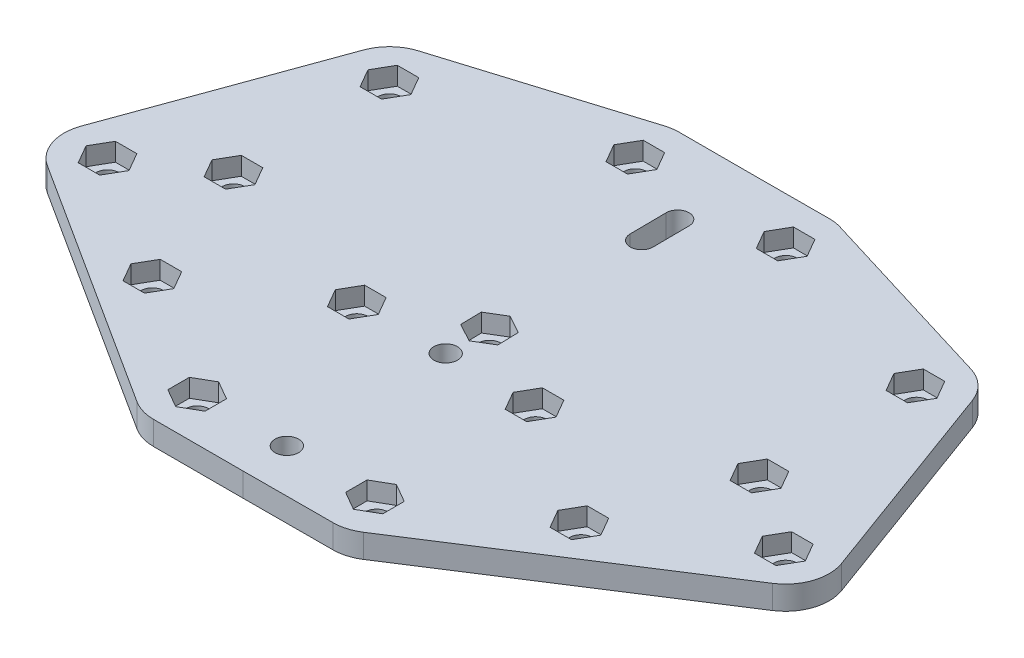
SolidWorks part; units mm, degrees
ref_plane "Front Plane" through (0, 0, 0) normal (0, 0, 1) x (1, 0, 0)
ref_plane "Top Plane" through (0, 0, 0) normal (0, 1, 0) x (1, 0, 0)
ref_plane "Right Plane" through (0, 0, 0) normal (1, 0, 0) x (0, 0, -1)
sketch "DimensionalReference" plane through (0, 0, 0) normal (0, 1, 0) x (1, 0, 0)
  line L0 (0, 0) -> (0, 54.3246) construction
  line L1 (-1000, 12.5) -> (1000, 12.5) construction
  line L2 (-1000, 12.5) -> (-1000, -12.5) construction
  line L3 (-1000, -12.5) -> (1000, -12.5) construction
  line L4 (1000, 12.5) -> (1000, -12.5) construction
  line L5 (-72.5, -22.5) -> (-72.5, 60.05) construction
  line L6 (0, 22.5) -> (0, -109.2175) construction
  line L7 (-12.5, -17.5) -> (12.9, -17.5) construction
  line L8 (-12.5, -17.5) -> (-12.5, -92.5) construction
  line L9 (-12.5, -92.5) -> (12.9, -92.5) construction
  line L10 (12.9, -17.5) -> (12.9, -92.5) construction
  line L11 (-104.4908, -32.4017) -> (-83.7785, 24.5983)
  line L12 (-23.5771, 48.153) -> (-76.0379, 31.9666)
  line L13 (-20.7123, 48.5) -> (20.7123, 48.5)
  line L14 (-93.2123, -36.5) -> (-24.5, -80.5) construction
  line L15 (-24.5, -80.5) -> (24.5, -80.5) construction
  line L16 (93.2123, -36.5) -> (24.5, -80.5) construction
  line L17 (104.4908, -32.4017) -> (83.7785, 24.5983)
  line L18 (23.5771, 48.153) -> (76.0379, 31.9666)
  line L19 (-12.5, -92.5) -> (-24.5, -92.5)
  line L20 (-99.6835, -46.6056) -> (-65.3273, -68.6056)
  line L21 (-65.3273, -68.6056) -> (-30.9712, -90.6056)
  line L22 (0.2, -92.5) -> (-12.5, -92.5)
  line L23 (99.6835, -46.6056) -> (65.3273, -68.6056)
  line L24 (65.3273, -68.6056) -> (30.9712, -90.6056)
  line L25 (12.5, -92.5) -> (24.5, -92.5)
  line L26 (-0.2, -92.5) -> (12.5, -92.5)
  circle A0 centre (0, 22.5) radius 12 construction
  circle A1 centre (-72.5, -22.5) radius 12 construction
  circle A2 centre (72.5, -22.5) radius 12 construction
  circle A3 centre (0, 22.5) radius 15 construction
  circle A4 centre (-72.5, -22.5) radius 15 construction
  circle A5 centre (72.5, -22.5) radius 15 construction
  circle A6 centre (0, 22.5) radius 25
  circle A7 centre (-72.5, -22.5) radius 25
  circle A8 centre (72.5, -22.5) radius 25
  circle A9 centre (-72.5, 20.5) radius 12
  circle A10 centre (-72.5, 20.5) radius 3.25
  circle A11 centre (-93.2123, -36.5) radius 12
  circle A12 centre (-20.7123, 36.5) radius 12
  circle A13 centre (-24.5, -36.5) radius 12
  circle A16 centre (72.5, 20.5) radius 12
  circle A17 centre (93.2123, -36.5) radius 12
  circle A18 centre (24.5, -36.5) radius 12
  circle A19 centre (20.7123, 36.5) radius 12
  circle A20 centre (-24.5, -80.5) radius 12
  circle A21 centre (24.5, -80.5) radius 12
  circle A22 centre (-58.8562, -58.5) radius 12
  circle A23 centre (58.8562, -58.5) radius 12
  point P0 (0, 0)
  point P24 (0, -262.4926)
  point P39 (0, 48.5)
  point P47 (0, -48.5)
  dimension "D3" = 24
  dimension "D10" = 24
  dimension "D11" = 24
  dimension "D13" = 30
  dimension "D14" = 30
  dimension "D15" = 30
  dimension "D16" = 50
  dimension "D17" = 50
  dimension "D18" = 50
  dimension "D19" = 24
  dimension "D21" = 6.5
  dimension "D22" = 24
  dimension "D29" = 24
  dimension "D31" = 12
  dimension "D32" = 12
  dimension "D1" = 2000
  dimension "D2" = 25
  dimension "D4" = 22.5
  dimension "D5" = 12.5
  dimension "D6" = 1000
  dimension "D7" = 145
  dimension "D8" = 72.5
  dimension "D9" = 22.5
  dimension "D12" = 22.5
  dimension "D20" = 8
  dimension "D23" = 24
  dimension "D24" = 24
  dimension "D25" = 25.4
  dimension "D26" = 75
  dimension "D27" = 12.5
  dimension "D28" = 5
  dimension "D30" = 12
sketch "Sketch2" plane through (0, 0, 0) normal (0, 1, 0) x (1, 0, 0)
  line L0 (24.8999, -92.4299) -> (0.2, -92.5)
  line L1 (-104.4908, -32.4017) -> (-83.7785, 24.5983)
  line L2 (-76.0379, 31.9666) -> (-24.9114, 47.7413)
  line L3 (0, 48.5) -> (-20.7123, 48.5)
  line L4 (-99.6835, -46.6056) -> (-30.9712, -90.6056)
  line L5 (0, 48.5) -> (0.2, -92.5) construction
  line L6 (-24.5, -92.5) -> (0.2, -92.5)
  line L7 (99.9529, -46.3225) -> (31.3657, -90.5172)
  line L8 (0, 48.5) -> (20.7122, 48.5588)
  line L9 (76.0845, 32.1824) -> (24.9134, 47.812)
  line L10 (104.7199, -32.1049) -> (83.8459, 24.8361)
  line L11 (-0.044, 27.5) -> (0.044, 17.5) construction
  line L12 (3.1059, 27.5277) -> (3.1938, 17.5277)
  line L13 (-3.1938, 27.4723) -> (-3.1059, 17.4723)
  line L28 (-24.5, -36.5) -> (24.5, -36.5) construction
  line L29 (-24.5, -80.5) -> (24.8659, -80.43) construction
  line L30 (0, 0) -> (139.3739, 0) construction
  arc A0 (-20.7123, 48.5) -> (-24.9114, 47.7413) centre (-20.7123, 36.5) ccw
  arc A6 (-30.9712, -90.6056) -> (-24.5, -92.5) centre (-24.5, -80.5) ccw
  arc A8 (-104.4908, -32.4017) -> (-99.6835, -46.6056) centre (-93.2123, -36.5) ccw
  arc A10 (-76.0379, 31.9666) -> (-83.7785, 24.5983) centre (-72.5, 20.5) ccw
  arc A11 (104.7199, -32.1049) -> (99.9529, -46.3225) centre (93.4531, -36.2352) cw
  arc A12 (76.0845, 32.1824) -> (83.8459, 24.8361) centre (72.5791, 20.7058) cw
  arc A13 (31.3657, -90.5172) -> (24.8999, -92.4299) centre (24.8659, -80.43) cw
  arc A14 (20.7122, 48.5588) -> (24.9134, 47.812) centre (20.7463, 36.5588) cw
  circle A15 centre (-72.5, 20.5) radius 3.15
  circle A16 centre (-20.7123, 36.5) radius 3.15
  circle A17 centre (-93.2123, -36.5) radius 3.15
  circle A18 centre (-58.8562, -58.5) radius 3.15
  circle A19 centre (-24.5, -80.5) radius 3.15
  circle A20 centre (-24.5, -36.5) radius 3.15
  circle A21 centre (-72.5, -22.5) radius 3.15
  arc A23 (3.1059, 27.5277) -> (-3.1938, 27.4723) centre (-0.044, 27.5) ccw
  arc A24 (-3.1059, 17.4723) -> (3.1938, 17.5277) centre (0.044, 17.5) ccw
  circle A25 centre (24.741, -36.4302) radius 3.15
  circle A26 centre (24.8659, -80.43) radius 3.15
  circle A27 centre (59.1595, -58.3326) radius 3.15
  circle A28 centre (93.4531, -36.2352) radius 3.15
  circle A29 centre (72.7011, -22.294) radius 3.15
  circle A30 centre (72.5791, 20.7058) radius 3.15
  circle A31 centre (20.7463, 36.5588) radius 3.15
  circle A32 centre (0, -36.5) radius 3.25
  circle A33 centre (0.1829, -80.465) radius 3.25
  circle A36 centre (0.1035, -24.5) radius 3.1
  point P22 (0, 22.5)
  dimension "D1" = 6.3
  dimension "D2" = 3.15
  dimension "D6" = 6.5
  dimension "D7" = 6.5
  dimension "D4" = 6.2
  dimension "D3" = 10
  dimension "D5" = 12
extrude "MainPlate" add sketch "Sketch2" along normal blind 6.5
sketch "Sketch8" plane through (0, 6.5, 0) normal (0, 1, 0) x (1, 0, 0)
  line L7 (-4.8355, -27.4899) -> (0.2234, -30.2723)
  line L8 (0.2234, -30.2723) -> (5.1624, -27.2824)
  line L9 (-18.5822, -36.5) -> (-21.5411, -31.375)
  line L10 (-21.5411, -31.375) -> (-27.4589, -31.375)
  line L11 (-27.4589, -31.375) -> (-30.4178, -36.5)
  line L12 (-30.4178, -36.5) -> (-27.4589, -41.625)
  line L13 (-27.4589, -41.625) -> (-21.5411, -41.625)
  line L14 (-21.5411, -41.625) -> (-18.5822, -36.5)
  line L15 (-66.5822, -22.5) -> (-69.5411, -17.375)
  line L16 (-69.5411, -17.375) -> (-75.4589, -17.375)
  line L17 (-75.4589, -17.375) -> (-78.4178, -22.5)
  line L18 (-78.4178, -22.5) -> (-75.4589, -27.625)
  line L19 (-75.4589, -27.625) -> (-69.5411, -27.625)
  line L20 (-69.5411, -27.625) -> (-66.5822, -22.5)
  line L21 (-66.5822, 20.5) -> (-69.5411, 25.625)
  line L22 (-69.5411, 25.625) -> (-75.4589, 25.625)
  line L23 (-75.4589, 25.625) -> (-78.4178, 20.5)
  line L24 (-78.4178, 20.5) -> (-75.4589, 15.375)
  line L25 (-75.4589, 15.375) -> (-69.5411, 15.375)
  line L26 (-69.5411, 15.375) -> (-66.5822, 20.5)
  line L27 (-87.2945, -36.5) -> (-90.2534, -31.375)
  line L28 (-90.2534, -31.375) -> (-96.1712, -31.375)
  line L29 (-96.1712, -31.375) -> (-99.1302, -36.5)
  line L30 (-99.1302, -36.5) -> (-96.1712, -41.625)
  line L31 (-96.1712, -41.625) -> (-90.2534, -41.625)
  line L32 (-90.2534, -41.625) -> (-87.2945, -36.5)
  line L33 (-52.9383, -58.5) -> (-55.8972, -53.375)
  line L34 (-55.8972, -53.375) -> (-61.8151, -53.375)
  line L35 (-61.8151, -53.375) -> (-64.774, -58.5)
  line L36 (-64.774, -58.5) -> (-61.8151, -63.625)
  line L37 (-61.8151, -63.625) -> (-55.8972, -63.625)
  line L38 (-55.8972, -63.625) -> (-52.9383, -58.5)
  line L39 (-24.5, -74.5822) -> (-29.625, -77.5411)
  line L40 (-29.625, -77.5411) -> (-29.625, -83.4589)
  line L41 (-29.625, -83.4589) -> (-24.5, -86.4178)
  line L42 (-24.5, -86.4178) -> (-19.375, -83.4589)
  line L43 (-19.375, -83.4589) -> (-19.375, -77.5411)
  line L44 (-19.375, -77.5411) -> (-24.5, -74.5822)
  line L45 (-14.7945, 36.5) -> (-17.7534, 41.625)
  line L46 (-17.7534, 41.625) -> (-23.6712, 41.625)
  line L47 (-23.6712, 41.625) -> (-26.6302, 36.5)
  line L48 (-26.6302, 36.5) -> (-23.6712, 31.375)
  line L49 (-23.6712, 31.375) -> (-17.7534, 31.375)
  line L50 (-17.7534, 31.375) -> (-14.7945, 36.5)
  line L51 (17.7534, 31.375) -> (14.7945, 36.5)
  line L52 (23.6712, 31.375) -> (17.7534, 31.375)
  line L53 (26.6302, 36.5) -> (23.6712, 31.375)
  line L54 (23.6712, 41.625) -> (26.6302, 36.5)
  line L55 (17.7534, 41.625) -> (23.6712, 41.625)
  line L56 (14.7945, 36.5) -> (17.7534, 41.625)
  line L57 (19.375, -77.5411) -> (24.5, -74.5822)
  line L58 (19.375, -83.4589) -> (19.375, -77.5411)
  line L59 (24.5, -86.4178) -> (19.375, -83.4589)
  line L60 (29.625, -83.4589) -> (24.5, -86.4178)
  line L61 (29.625, -77.5411) -> (29.625, -83.4589)
  line L62 (24.5, -74.5822) -> (29.625, -77.5411)
  line L63 (55.8972, -63.625) -> (52.9383, -58.5)
  line L64 (61.8151, -63.625) -> (55.8972, -63.625)
  line L65 (64.774, -58.5) -> (61.8151, -63.625)
  line L66 (61.8151, -53.375) -> (64.774, -58.5)
  line L67 (55.8972, -53.375) -> (61.8151, -53.375)
  line L68 (52.9383, -58.5) -> (55.8972, -53.375)
  line L69 (90.2534, -41.625) -> (87.2945, -36.5)
  line L70 (96.1712, -41.625) -> (90.2534, -41.625)
  line L71 (99.1302, -36.5) -> (96.1712, -41.625)
  line L72 (96.1712, -31.375) -> (99.1302, -36.5)
  line L73 (90.2534, -31.375) -> (96.1712, -31.375)
  line L74 (87.2945, -36.5) -> (90.2534, -31.375)
  line L75 (69.5411, 15.375) -> (66.5822, 20.5)
  line L76 (75.4589, 15.375) -> (69.5411, 15.375)
  line L77 (78.4178, 20.5) -> (75.4589, 15.375)
  line L78 (75.4589, 25.625) -> (78.4178, 20.5)
  line L79 (69.5411, 25.625) -> (75.4589, 25.625)
  line L80 (66.5822, 20.5) -> (69.5411, 25.625)
  line L81 (69.5411, -27.625) -> (66.5822, -22.5)
  line L82 (75.4589, -27.625) -> (69.5411, -27.625)
  line L83 (78.4178, -22.5) -> (75.4589, -27.625)
  line L84 (75.4589, -17.375) -> (78.4178, -22.5)
  line L85 (69.5411, -17.375) -> (75.4589, -17.375)
  line L86 (66.5822, -22.5) -> (69.5411, -17.375)
  line L87 (21.5411, -41.625) -> (18.5822, -36.5)
  line L88 (27.4589, -41.625) -> (21.5411, -41.625)
  line L89 (30.4178, -36.5) -> (27.4589, -41.625)
  line L90 (27.4589, -31.375) -> (30.4178, -36.5)
  line L91 (21.5411, -31.375) -> (27.4589, -31.375)
  line L92 (18.5822, -36.5) -> (21.5411, -31.375)
  line L93 (5.1624, -27.2824) -> (5.0426, -21.5101)
  line L94 (5.0426, -21.5101) -> (-0.0163, -18.7277)
  line L95 (-0.0163, -18.7277) -> (-4.9553, -21.7176)
  line L96 (-4.9553, -21.7176) -> (-4.8355, -27.4899)
  circle A0 centre (0.1035, -24.5) radius 5 construction
  circle A1 centre (-24.5, -36.5) radius 5.125 construction
  circle A2 centre (-72.5, -22.5) radius 5.125 construction
  circle A3 centre (-72.5, 20.5) radius 5.125 construction
  circle A4 centre (-93.2123, -36.5) radius 5.125 construction
  circle A5 centre (-58.8562, -58.5) radius 5.125 construction
  circle A6 centre (-24.5, -80.5) radius 5.125 construction
  circle A7 centre (-20.7123, 36.5) radius 5.125 construction
  circle A8 centre (20.7123, 36.5) radius 5.125 construction
  circle A9 centre (24.5, -80.5) radius 5.125 construction
  circle A10 centre (58.8562, -58.5) radius 5.125 construction
  circle A11 centre (93.2123, -36.5) radius 5.125 construction
  circle A12 centre (72.5, 20.5) radius 5.125 construction
  circle A13 centre (72.5, -22.5) radius 5.125 construction
  circle A14 centre (24.5, -36.5) radius 5.125 construction
  point P2 (2.6929, -28.7773)
  dimension "D1" = 10
  dimension "D2" = 10.25
  dimension "D3" = 10.25
  dimension "D4" = 10.25
  dimension "D5" = 10.25
  dimension "D6" = 10.25
  dimension "D7" = 10.25
  dimension "D8" = 10.25
extrude "PressFitNuts" cut sketch "Sketch8" against normal blind 5
sketch "Sketch9" plane through (0, 6.5, 0) normal (0, 1, 0) x (1, 0, 0)
  line L0 (52.6627, -41.5446) -> (50.906, -42.448)
  line L1 (46.1928, -40.9361) -> (17.801, 14.2744)
  line L2 (20.9136, 19.375) -> (51.1306, 19.375)
  line L3 (54.6306, 15.8706) -> (54.562, -38.4365)
  line L4 (0.2, -92.5) -> (0.1035, -24.5) construction
  line L5 (0, 48.5) -> (-20.7123, 48.5) construction
  line L8 (1.0348, -68.2409) -> (25.7237, -61.874)
  line L9 (25.7235, -55.0957) -> (1.0165, -48.7258)
  line L10 (75.4589, -17.375) -> (69.5411, -17.375) construction
  line L11 (17.7534, 31.375) -> (23.6712, 31.375) construction
  line L12 (104.7199, -32.1049) -> (83.8459, 24.8361) construction
  line L13 (3.1938, 17.5277) -> (3.1059, 27.5277) construction
  line L14 (72.4743, -5.375) -> (70.1082, -5.375)
  line L15 (66.6082, -1.8706) -> (66.6107, 0.0995)
  line L16 (72.3516, 2.7836) -> (74.7152, 0.8136)
  line L21 (73.0837, -41.5737) -> (69.4223, -40.2688)
  line L22 (68.257, -41.7691) -> (72.4275, -47.9662)
  line L23 (74.1008, -47.9448) -> (74.8613, -46.7499)
  line L24 (87.2945, -36.5) -> (90.2534, -41.625) construction
  line L25 (64.774, -58.5) -> (61.8151, -53.375) construction
  line L26 (31.3657, -90.5172) -> (99.9529, -46.3225) construction
  line L27 (-73.8269, -48.1547) -> (-74.5908, -46.9619)
  line L28 (-68.0006, -41.9624) -> (-72.1536, -48.1713)
  line L29 (-72.8278, -41.7807) -> (-69.1702, -40.4654)
  line L31 (-72.2216, 2.5786) -> (-74.5796, 0.6018)
  line L32 (-66.465, -2.0593) -> (-66.4731, -0.0893)
  line L33 (-72.3212, -5.5804) -> (-69.9551, -5.5737)
  line L34 (-25.4295, -55.1682) -> (-0.7407, -48.7283)
  line L35 (-0.7036, -68.2434) -> (-25.4105, -61.9465)
  line L38 (-54.5378, 15.7157) -> (-54.3152, -38.5909)
  line L39 (-20.8309, 19.3158) -> (-51.0478, 19.2301)
  line L40 (-45.9389, -41.0668) -> (-17.7039, 14.224)
  line L41 (-52.407, -41.6937) -> (-50.6478, -42.5921)
  line L42 (0.0562, 8.8531) -> (0, 48.5) construction
  circle A0 centre (0, -36.5) radius 3.25 construction
  circle A1 centre (0.1829, -80.465) radius 3.25 construction
  circle A2 centre (0.1829, -80.465) radius 3.25 construction
  circle A3 centre (0.2411, -36.4997) radius 3.25 construction
  arc A4 (-20.8309, 19.3158) -> (-17.7039, 14.224) centre (-20.821, 15.8158) cw
  arc A5 (-54.5378, 15.7157) -> (-51.0478, 19.2301) centre (-51.0378, 15.7301) cw
  arc A6 (-74.5796, 0.6018) -> (-72.3212, -5.5804) centre (-72.3311, -2.0804) ccw
  arc A7 (-72.2216, 2.5786) -> (-66.4731, -0.0893) centre (-69.9731, -0.1036) cw
  arc A8 (-66.465, -2.0593) -> (-69.9551, -5.5737) centre (-69.965, -2.0737) cw
  arc A9 (-74.5908, -46.9619) -> (-72.8278, -41.7807) centre (-71.6435, -45.0742) cw
  arc A10 (-54.3152, -38.5909) -> (-52.407, -41.6937) centre (-50.8152, -38.5766) ccw
  arc A11 (-45.9389, -41.0668) -> (-50.6478, -42.5921) centre (-49.056, -39.475) cw
  arc A12 (-25.4295, -55.1682) -> (-25.4105, -61.9465) centre (-24.5461, -58.5549) ccw
  arc A13 (25.7237, -61.874) -> (25.7235, -55.0957) centre (24.8497, -58.4849) ccw
  arc A14 (1.0348, -68.2409) -> (-0.7036, -68.2434) centre (0.1608, -64.8518) cw
  arc A15 (1.0165, -48.7258) -> (-0.7407, -48.7283) centre (0.1427, -52.115) ccw
  arc A21 (17.801, 14.2744) -> (20.9136, 19.375) centre (20.9136, 15.875) cw
  arc A22 (51.1306, 19.375) -> (54.6306, 15.8706) centre (51.1306, 15.875) cw
  arc A23 (50.906, -42.448) -> (46.1928, -40.9361) centre (49.3054, -39.3355) cw
  arc A24 (52.6627, -41.5446) -> (54.562, -38.4365) centre (51.062, -38.4321) ccw
  arc A25 (73.0837, -41.5737) -> (74.8613, -46.7499) centre (71.9087, -44.8706) cw
  arc A26 (66.6107, 0.0995) -> (72.3516, 2.7836) centre (70.1107, 0.0951) cw
  arc A27 (70.1082, -5.375) -> (66.6082, -1.8706) centre (70.1082, -1.875) cw
  arc A28 (72.4743, -5.375) -> (74.7152, 0.8136) centre (72.4743, -1.875) ccw
  arc A29 (-73.8269, -48.1547) -> (-72.1536, -48.1713) centre (-72.9848, -47.6153) ccw
  arc A30 (-68.0006, -41.9624) -> (-69.1702, -40.4654) centre (-68.8318, -41.4064) ccw
  arc A31 (72.4275, -47.9662) -> (74.1008, -47.9448) centre (73.2571, -47.4079) ccw
  arc A32 (69.4223, -40.2688) -> (68.257, -41.7691) centre (69.0866, -41.2108) ccw
  point P72 (-15.0954, 19.3321)
  point P75 (-54.5522, 19.2201)
  point P78 (-81.9869, -5.6078)
  point P81 (-66.5037, 7.372)
  point P84 (-66.4507, -5.5637)
  point P87 (-76.9581, -43.2658)
  point P90 (-54.3064, -40.7237)
  point P93 (-47.5307, -44.1838)
  point P96 (-38.5637, -58.5942)
  point P99 (38.8673, -58.4844)
  point P102 (0.1659, -68.465)
  point P105 (0.1376, -48.4992)
  point P108 (0.0559, 9.0631)
  point P111 (-8.3883, 6.0805)
  point P114 (-11.4986, -24.5329)
  point P117 (11.7057, -24.5)
  point P120 (8.5087, 6.1045)
  point P123 (15.1781, 19.375)
  point P126 (54.635, 19.375)
  point P129 (47.7934, -44.0486)
  point P132 (54.5593, -40.5693)
  point P135 (77.2181, -43.0472)
  point P138 (66.6201, 7.5608)
  point P141 (66.6038, -5.375)
  point P144 (82.1401, -5.375)
  point P147 (-73.0029, -49.4411)
  point P150 (-66.3118, -39.4376)
  point P153 (73.2805, -49.2336)
  point P156 (66.561, -39.2491)
  dimension "D25" = 3.5
  dimension "D26" = 1
  dimension "D1" = 12
  dimension "D2" = 12
  dimension "D3" = 12
  dimension "D4" = 12
  dimension "D5" = 12
  dimension "D6" = 12
  dimension "D7" = 12
  dimension "D8" = 12
  dimension "D9" = 8.3423
  dimension "D10" = 12
  dimension "D11" = 12
  dimension "D13" = 12
  dimension "D14" = 12
  dimension "D15" = 12
  dimension "D16" = 12
  dimension "D17" = 12
  dimension "D18" = 12
  dimension "D19" = 12
  dimension "D20" = 12
  dimension "D21" = 12
  dimension "D22" = 12
  dimension "D23" = 12
  dimension "D24" = 12
sketch "Sketch11" plane through (0, 0, 0) normal (0, 1, 0) x (1, 0, 0)
  line L0 (0, -4.5) -> (0, 116.15) construction
  line L1 (-111.9, 4.5) -> (-111.9, -116.15)
  line L2 (-86.5, 4.5) -> (-86.5, -19)
  line L3 (-111.9, -116.15) -> (-86.5, -116.15)
  line L4 (86.5, 4.5) -> (86.5, 44.5764)
  line L5 (-86.5, 4.5) -> (-86.5, 44.5764)
  line L6 (-86.5, 44.5764) -> (-111.9, 44.5764)
  line L7 (-111.9, 4.5) -> (-111.9, 44.5764)
  line L8 (-86.5, -116.15) -> (-36.5, -116.15)
  line L9 (-66.5, -39) -> (-56.5, -39)
  line L10 (-36.5, -116.15) -> (-36.5, -59)
  line L11 (86.5, 44.5764) -> (111.9, 44.5764)
  line L12 (111.9, 4.5) -> (111.9, 44.5764)
  line L13 (111.9, 4.5) -> (111.9, -116.15)
  line L14 (111.9, -116.15) -> (86.5, -116.15)
  line L15 (86.5, -116.15) -> (36.5, -116.15)
  line L16 (36.5, -116.15) -> (36.5, -59)
  line L17 (66.5, -39) -> (56.5, -39)
  line L18 (86.5, 4.5) -> (86.5, -19)
  circle A0 centre (-24.5, -85) radius 3.15 construction
  circle A1 centre (-72.5, -27) radius 3.15 construction
  arc A2 (-56.5, -39) -> (-36.5, -59) centre (-56.5, -59) cw
  arc A3 (-86.5, -19) -> (-66.5, -39) centre (-66.5, -19) ccw
  arc A4 (56.5, -39) -> (36.5, -59) centre (56.5, -59) ccw
  arc A5 (86.5, -19) -> (66.5, -39) centre (66.5, -19) cw
move or copy body "Body-Move/Copy1" [suppressed] bodies to move or copy 106
